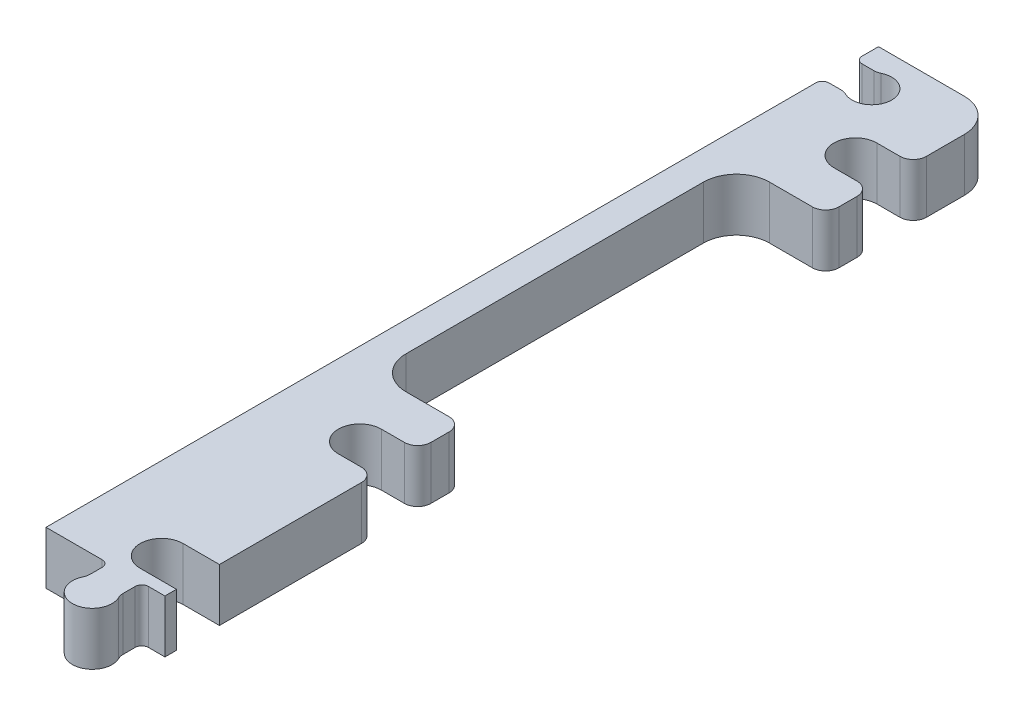
SolidWorks part; units mm, degrees
ref_plane "정면" through (0, 0, 0) normal (0, 0, 1) x (1, 0, 0)
ref_plane "윗면" through (0, 0, 0) normal (0, 1, 0) x (1, 0, 0)
ref_plane "우측면" through (0, 0, 0) normal (1, 0, 0) x (0, 0, -1)
sketch "스케치1" plane through (0, 0, 0) normal (0, 1, 0) x (1, 0, 0)
  line L1 (0, 0) -> (18, 0)
  line L2 (0, 0) -> (0, 126)
  line L3 (0, 126) -> (18, 126)
  line L4 (18, 0) -> (18, 126)
  dimension "D1" = 126
  dimension "D2" = 18
extrude "보스-돌출1" add sketch "스케치1" along normal blind 8
sketch "스케치5" plane through (0, 8, 0) normal (0, 1, 0) x (1, 0, 0)
  line L0 (18, 0) -> (18, 126) construction
  line L1 (18, 100) -> (4.5, 100)
  line L2 (18, 100) -> (18, 45)
  line L3 (18, 45) -> (4.5, 45)
  line L4 (4.5, 100) -> (4.5, 45)
  line L5 (0, 126) -> (0, 0) construction
  line L7 (18, 126) -> (0, 126) construction
  dimension "D1" = 4.5
  dimension "D2" = 26
  dimension "D3" = 55
extrude "컷-돌출3" cut sketch "스케치5" against normal blind 10
sketch "스케치2" plane through (0, 8, 0) normal (0, 1, 0) x (1, 0, 0)
  line L1 (18, 100) -> (4.5, 100) construction
  line L2 (12.5, 113) -> (12.5, 110) construction
  line L3 (12.5, 110) -> (12.5, 35) construction
  line L4 (12.5, 35) -> (12.5, 0) construction
  line L5 (0, 0) -> (18, 0) construction
  line L6 (4.5, 45) -> (18, 45) construction
  line L7 (12.5, 5) -> (18, 5) construction
  line L8 (18, 0) -> (18, 45) construction
  line L9 (12.5, 8.25) -> (18, 8.25)
  line L10 (18, 0) -> (18, 45) construction
  line L11 (12.5, 1.75) -> (18, 1.75)
  line L14 (12.5, 110) -> (18, 110) construction
  line L15 (12.5, 113.25) -> (18, 113.25)
  line L16 (12.5, 106.75) -> (18, 106.75)
  line L17 (12.5, 35) -> (18, 35) construction
  line L18 (12.5, 38.25) -> (18, 38.25)
  line L19 (12.5, 31.75) -> (18, 31.75)
  line L20 (0, 126) -> (0, 0) construction
  arc A0 (12.5, 8.25) -> (12.5, 1.75) centre (12.5, 5) ccw
  arc A1 (18, 1.75) -> (18, 8.25) centre (18, 5) ccw
  arc A2 (12.5, 113.25) -> (12.5, 106.75) centre (12.5, 110) ccw
  arc A3 (18, 106.75) -> (18, 113.25) centre (18, 110) ccw
  arc A4 (12.5, 38.25) -> (12.5, 31.75) centre (12.5, 35) ccw
  arc A5 (18, 31.75) -> (18, 38.25) centre (18, 35) ccw
  point P16 (15.25, 5)
  point P18 (15.25, 110)
  point P24 (15.25, 35)
  dimension "D2" = 3.25
  dimension "D1" = 10
  dimension "D3" = 12.5
  dimension "D4" = 10
  dimension "D5" = 30
extrude "컷-돌출1" cut sketch "스케치2" against normal blind 10
fillet "필렛1" radius 5 2 edges at (4.5, 4, -100) (4.5, 4, -45)
fillet "필렛2" radius 5 1 edges at (18, 4, -126)
fillet "필렛3" radius 2 6 edges at (18, 4, -113.25) (18, 4, -106.75) (18, 4, -100) (18, 4, -31.75) (18, 4, -45) (18, 4, -38.25)
sketch "스케치6" plane through (0, 0, 0) normal (0, -1, 0) x (1, 0, 0)
  line L0 (5, -120) -> (0, -120) construction
  line L3 (3.3417, -122.5) -> (3.3417, -120) construction
  line L4 (0, -117.5) -> (2.8206, -117.5)
  line L5 (0, -117.5) -> (0, -122.5)
  line L6 (0, -122.5) -> (2.8206, -122.5)
  line L7 (3.3417, -120) -> (3.3417, -117.5) construction
  line L8 (0, -117.5) -> (3.3417, -122.5) construction
  line L9 (0, -122.5) -> (3.3417, -117.5) construction
  line L10 (13, -126) -> (0, -126) construction
  arc A0 (3.6923, -122.7) -> (3.6923, -117.3) centre (5, -120) ccw
  arc A1 (2.8206, -117.5) -> (3.6923, -117.3) centre (2.8206, -115.5) ccw
  arc A2 (2.8206, -122.5) -> (3.6923, -122.7) centre (2.8206, -124.5) cw
  point P3 (1.6708, -120)
  dimension "D4" = 2
  dimension "D5" = 6
  dimension "D3" = 6
  dimension "D1" = 5
  dimension "D2" = 5
extrude "컷-돌출4" cut sketch "스케치6" against normal blind 8
sketch "스케치7" plane through (0, 0, 0) normal (0, -1, 0) x (1, 0, 0)
  line L0 (12, 5) -> (12, 0) construction
  line L1 (14.5, 3.3417) -> (12, 3.3417) construction
  line L2 (9.5, 0) -> (9.5, 2.8206)
  line L3 (9.5, 0) -> (14.5, 0)
  line L4 (14.5, 0) -> (14.5, 2.8206)
  line L5 (12, 3.3417) -> (9.5, 3.3417) construction
  line L6 (9.5, 0) -> (14.5, 3.3417) construction
  line L7 (14.5, 0) -> (9.5, 3.3417) construction
  line L8 (0, 0) -> (18, 0) construction
  line L9 (14.5, 1) -> (14.5, 2.8206) construction
  arc A0 (14.7, 3.6923) -> (9.3, 3.6923) centre (12, 5) ccw
  arc A1 (9.5, 2.8206) -> (9.3, 3.6923) centre (7.5, 2.8206) ccw
  arc A2 (14.5, 2.8206) -> (14.7, 3.6923) centre (16.5, 2.8206) cw
  point P3 (12, 1.6708)
  point P14 (14.5, 0)
  dimension "D3" = 6
  dimension "D4" = 2
  dimension "D1" = 5
  dimension "D2" = 5
extrude "보스-돌출3" add sketch "스케치7" against normal blind 8
fillet "필렛4" radius 1 4 edges at (0, 4, -117.5) (0, 4, -122.5)
